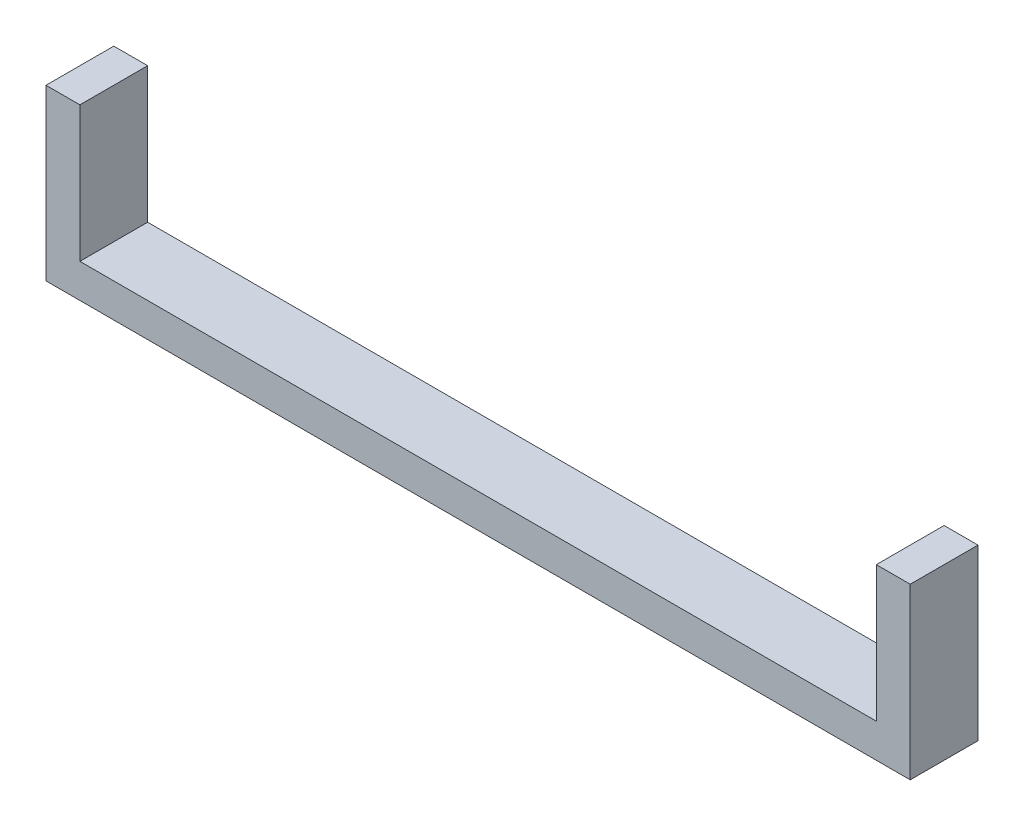
SolidWorks part; units mm, degrees
ref_plane "Front Plane" through (0, 0, 0) normal (0, 0, 1) x (1, 0, 0)
ref_plane "Top Plane" through (0, 0, 0) normal (0, 1, 0) x (1, 0, 0)
ref_plane "Right Plane" through (0, 0, 0) normal (1, 0, 0) x (0, 0, -1)
sketch "Sketch1" plane through (0, 0, 0) normal (0, 0, 1) x (1, 0, 0)
  line L0 (0, 0) -> (323.85, 0)
  line L1 (323.85, 0) -> (323.85, 63.5)
  line L2 (323.85, 63.5) -> (311.15, 63.5)
  line L3 (311.15, 63.5) -> (311.15, 12.7)
  line L4 (311.15, 12.7) -> (12.7, 12.7)
  line L5 (12.7, 12.7) -> (12.7, 63.5)
  line L6 (12.7, 63.5) -> (0, 63.5)
  line L7 (0, 63.5) -> (0, 0)
  dimension "D1" = 12.7
  dimension "D2" = 12.7
  dimension "D3" = 298.45
  dimension "D4" = 50.8
  dimension "D5" = 63.5
extrude "Boss-Extrude1" add sketch "Sketch1" along normal blind 25.4
